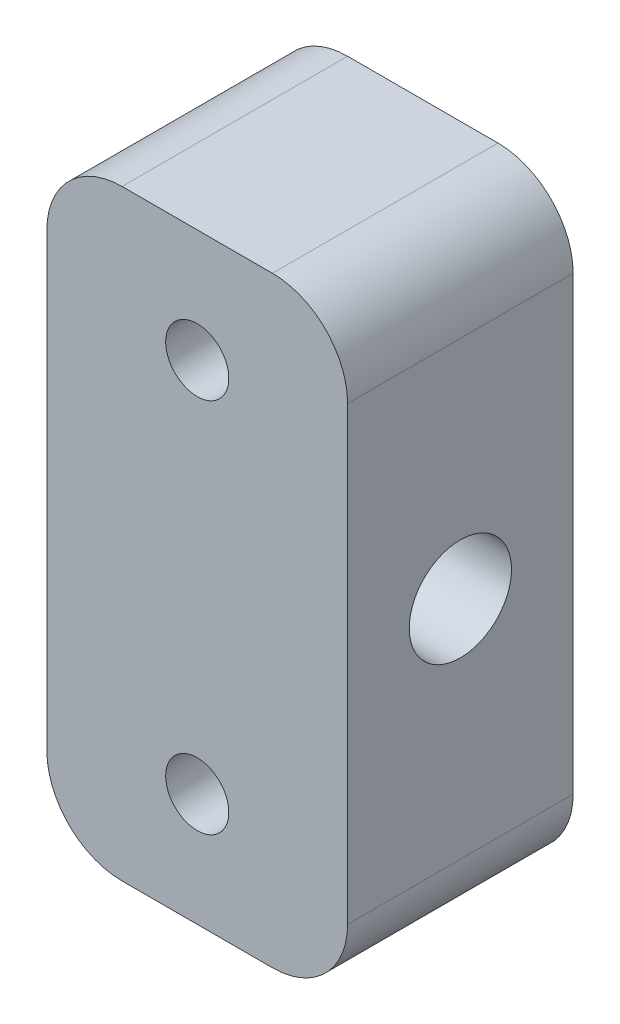
SolidWorks part; units mm, degrees
material "6063-T6"
ref_plane "Ön Düzlem" through (0, 0, 0) normal (0, 0, 1) x (1, 0, 0)
ref_plane "Üst Düzlem" through (0, 0, 0) normal (0, 1, 0) x (1, 0, 0)
ref_plane "Sağ Düzlem" through (0, 0, 0) normal (1, 0, 0) x (0, 0, -1)
sketch "Çizim1" plane through (0, 0, 0) normal (0, 0, 1) x (1, 0, 0)
  line L1 (-10, -20) -> (10, -20)
  line L2 (-10, -20) -> (-10, 20)
  line L3 (-10, 20) -> (10, 20)
  line L4 (10, -20) -> (10, 20)
  line L5 (-10, -20) -> (10, 20) construction
  line L6 (-10, 20) -> (10, -20) construction
  point P0 (0, 0)
  dimension "D1" = 20
  dimension "D2" = 40
extrude "Yükseklik-Ekstrüzyon1" add sketch "Çizim1" along normal mid plane 15
fillet "Radyus1" radius 5 4 edges at (-10, 20, 0) (10, 20, 0) (10, -20, 0) (-10, -20, 0)
sketch "Çizim2" plane through (0, 0, -7.5) normal (0, 0, -1) x (-1, 0, 0)
  line L0 (0, -12.5) -> (0, 12.5) construction
  point P4 (0, 0)
  dimension "D1" = 25
hole_wizard "M5 Dişli Delik1" positions "3B Çizim1" profile "Çizim3" tap size "M5" standard "ISO" end condition through all
sketch3d "3B Çizim1"
  point P0 (0, 12.5, -7.5)
  point P3 (0, -12.5, -7.5)
sketch "Çizim3" plane through (0, 12.5, -7.5) normal (1, 0, 0) x (0, 1, 0)
  line L0 (0, 0) -> (0, 15)
  line L1 (0, 15) -> (2.1, 15)
  line L2 (2.1, 15) -> (2.1, 0)
  line L5 (2.1, 0) -> (0, 0)
  line L11 (0, -6.35) -> (0, 107.95) construction
  dimension "Thru Tap Drill Dia." = 4.2
  dimension "Thru Tap Drill Depth" = 15
cosmetic thread "Delik Dişi1" parameters "D2"=5
cosmetic thread "Delik Dişi2" parameters "D2"=5
sketch "Çizim13" plane through (-10, 0, 0) normal (-1, 0, 0) x (0, 0, 1)
  line L0 (-3.6858, 0) -> (3.6858, 0) construction
  line L1 (0, 11.3051) -> (0, -3.4383) construction
  point P4 (0, 0)
  point P8 (0, 3.9334)
hole_wizard "M8 Dişli Delik1" positions "Çizim14" profile "Çizim15" tap size "M8" standard "ISO" end condition through all
sketch "Çizim14" plane through (-10, 0, 0) normal (-1, 0, 0) x (0, 0, 1)
  point P0 (0, 0)
sketch "Çizim15" plane through (-10, 0, 0) normal (0, 1, 0) x (0, 0, 1)
  line L0 (0, 0) -> (0, 20)
  line L1 (0, 20) -> (3.4, 20)
  line L2 (3.4, 20) -> (3.4, 0)
  line L5 (3.4, 0) -> (0, 0)
  line L11 (0, -6.35) -> (0, 107.95) construction
  dimension "Thru Tap Drill Dia." = 6.8
  dimension "Thru Tap Drill Depth" = 20
cosmetic thread "Delik Dişi3" parameters "D2"=8
